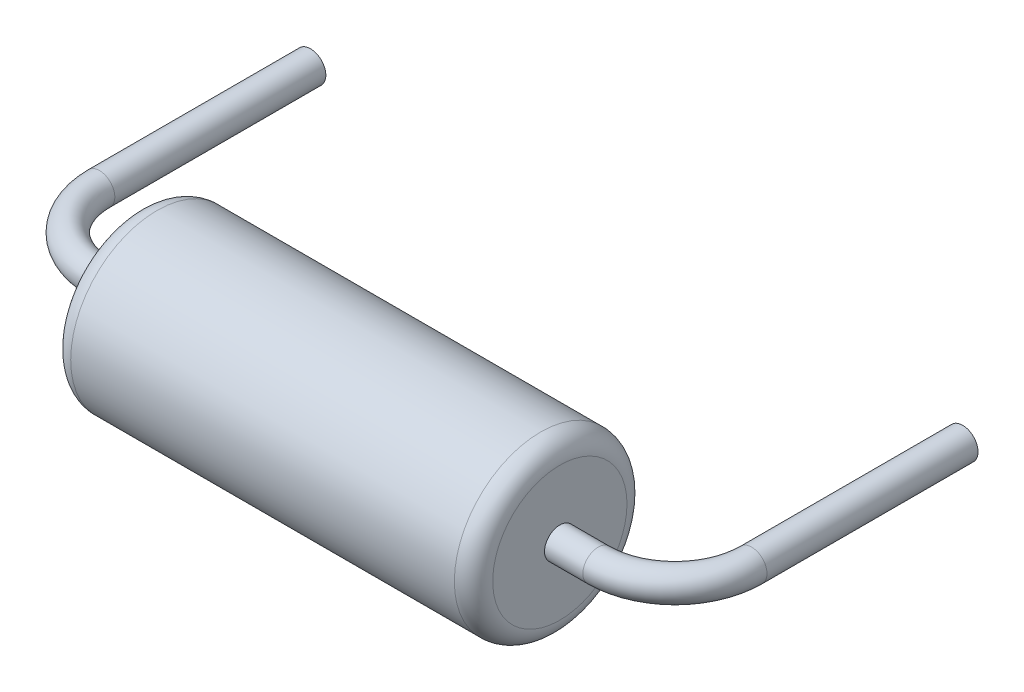
SolidWorks part; units mm, degrees
ref_plane "Front" through (0, 0, 0) normal (0, 0, 1) x (1, 0, 0)
ref_plane "Top" through (0, 0, 0) normal (0, 1, 0) x (1, 0, 0)
ref_plane "Right" through (0, 0, 0) normal (1, 0, 0) x (0, 0, -1)
sketch "Эскиз1" plane through (0, 0, 0) normal (0, 0, 1) x (1, 0, 0)
  line L1 (-1, -1) -> (1, -1)
  line L2 (-1, -1) -> (-1, 1)
  line L3 (-1, 1) -> (1, 1)
  line L4 (1, -1) -> (1, 1)
  line L5 (16, -1) -> (18, -1)
  line L6 (16, -1) -> (16, 1)
  line L7 (16, 1) -> (18, 1)
  line L8 (18, -1) -> (18, 1)
ref_plane "Плоскость1" through (3, 0, 0) normal (1, 0, 0) x (0, 0, -1)
sketch "Эскиз3" plane through (3, 0, 0) normal (1, 0, 0) x (0, 0, -1)
  line L0 (-2.25, 0) -> (0, 0) construction
  circle A0 centre (-2.25, 0) radius 2.25
  dimension "D1" = 4.5
extrude "Вытянуть1" add sketch "Эскиз3" along normal blind 11
ref_plane "Плоскость2" through (0, 0, -5.25) normal (0, 0, 1) x (1, 0, 0)
sketch "Эскиз4" plane through (0, 0, -5.25) normal (0, 0, 1) x (1, 0, 0)
  circle A0 centre (0, 0) radius 0.4
  dimension "D1" = 0.8
sketch "Эскиз5" plane through (0, 0, 0) normal (0, 1, 0) x (1, 0, 0)
  line L0 (0, 5.25) -> (0, -0.25)
  line L1 (2, -2.25) -> (2.9658, -2.25)
  line L2 (14, -2.25) -> (3, -2.25) construction
  line L3 (2.9658, -2.25) -> (14, -2.25)
  line L4 (14, -2.25) -> (15, -2.25)
  line L5 (17, -0.25) -> (17, 0)
  line L6 (16, 0) -> (18, 0) construction
  line L7 (17, 0) -> (17, 5.25)
  arc A0 (0, -0.25) -> (2, -2.25) centre (2, -0.25) ccw
  arc A1 (15, -2.25) -> (17, -0.25) centre (15, -0.25) ccw
  point P14 (0, -2.25)
  point P17 (17, -2.25)
  dimension "D1" = 2
  dimension "D2" = 2
sweep "По траектории1" add profiles "Эскиз4" path "Эскиз5"
fillet "Скругление1" radius 0.5
